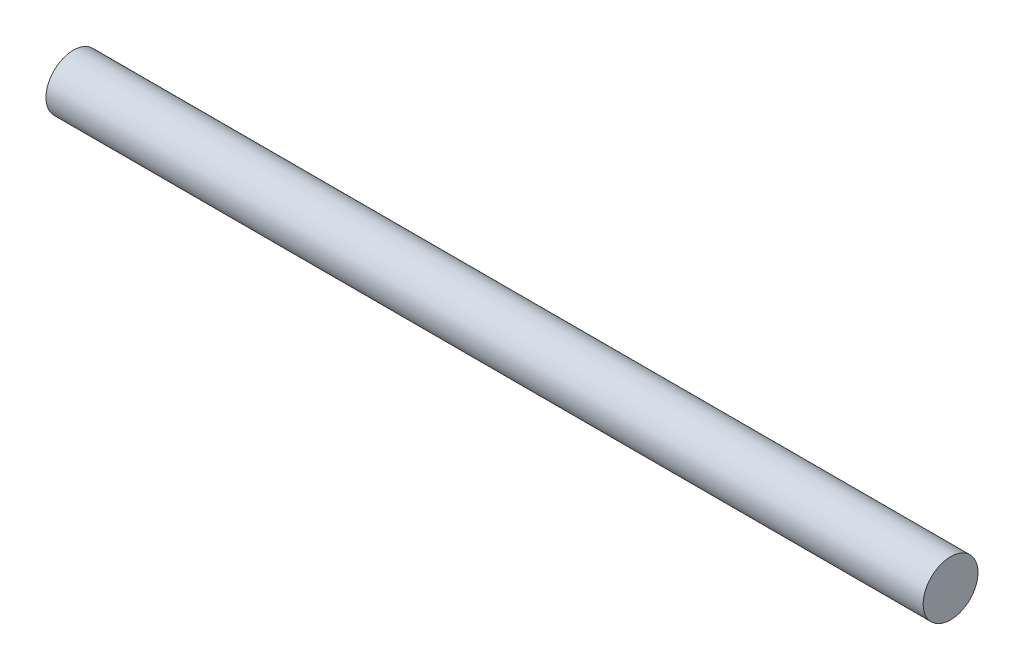
SolidWorks part; units mm, degrees
material "Chrome Stainless Steel"
ref_plane "Front Plane" through (0, 0, 0) normal (0, 0, 1) x (1, 0, 0)
ref_plane "Top Plane" through (0, 0, 0) normal (0, 1, 0) x (1, 0, 0)
ref_plane "Right Plane" through (0, 0, 0) normal (1, 0, 0) x (0, 0, -1)
sketch "BaseS" plane through (0, 0, 0) normal (1, 0, 0) x (0, 0, -1)
  circle A0 centre (0, 0) radius 1.25
  dimension "Diameter" = 2.5
extrude "Base" add sketch "BaseS" along normal mid plane 40
